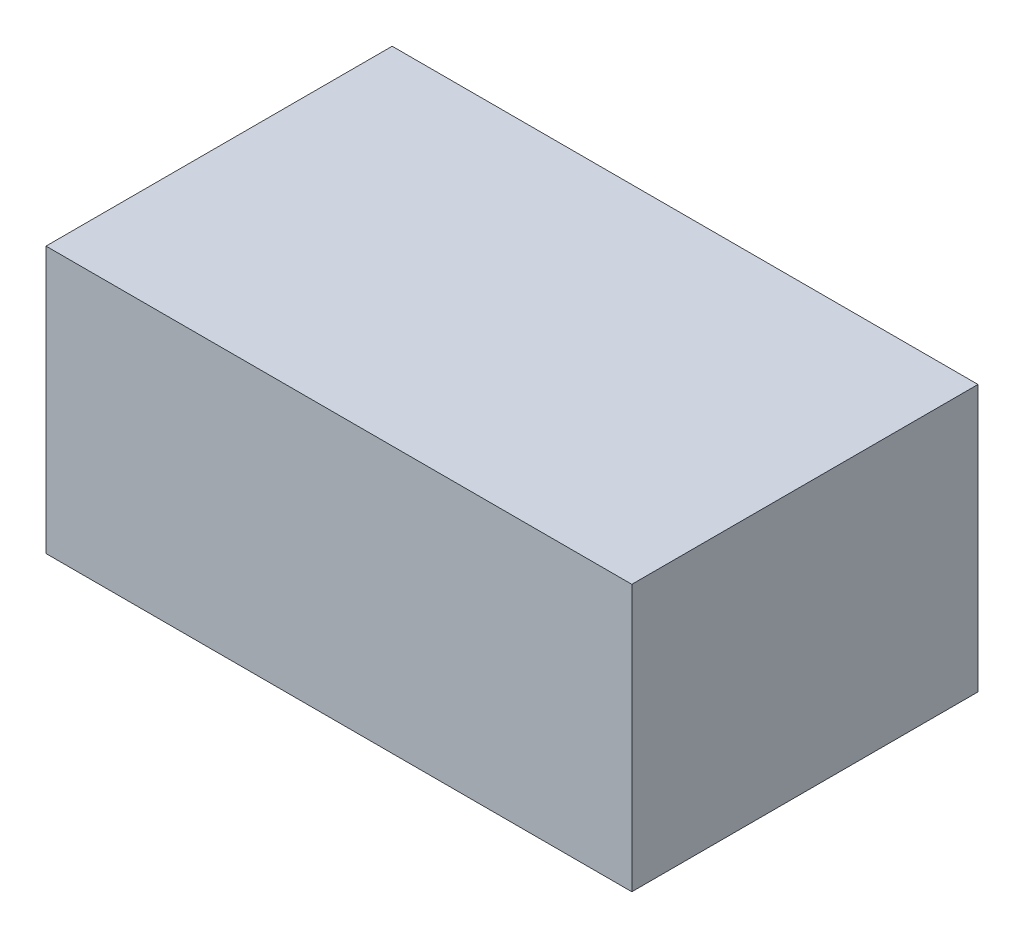
SolidWorks part; units mm, degrees
ref_plane "Front Plane" through (0, 0, 0) normal (0, 0, 1) x (1, 0, 0)
ref_plane "Top Plane" through (0, 0, 0) normal (0, 1, 0) x (1, 0, 0)
ref_plane "Right Plane" through (0, 0, 0) normal (1, 0, 0) x (0, 0, -1)
sketch "Sketch2" plane through (0, 0, 0) normal (0, 1, 0) x (1, 0, 0)
  line L1 (-13.97, -8.255) -> (13.97, -8.255)
  line L2 (-13.97, -8.255) -> (-13.97, 8.255)
  line L3 (-13.97, 8.255) -> (13.97, 8.255)
  line L4 (13.97, -8.255) -> (13.97, 8.255)
  line L5 (-13.97, -8.255) -> (13.97, 8.255) construction
  line L6 (-13.97, 8.255) -> (13.97, -8.255) construction
  point P0 (0, 0)
extrude "Boss-Extrude1" add sketch "Sketch2" along normal blind 12.7
